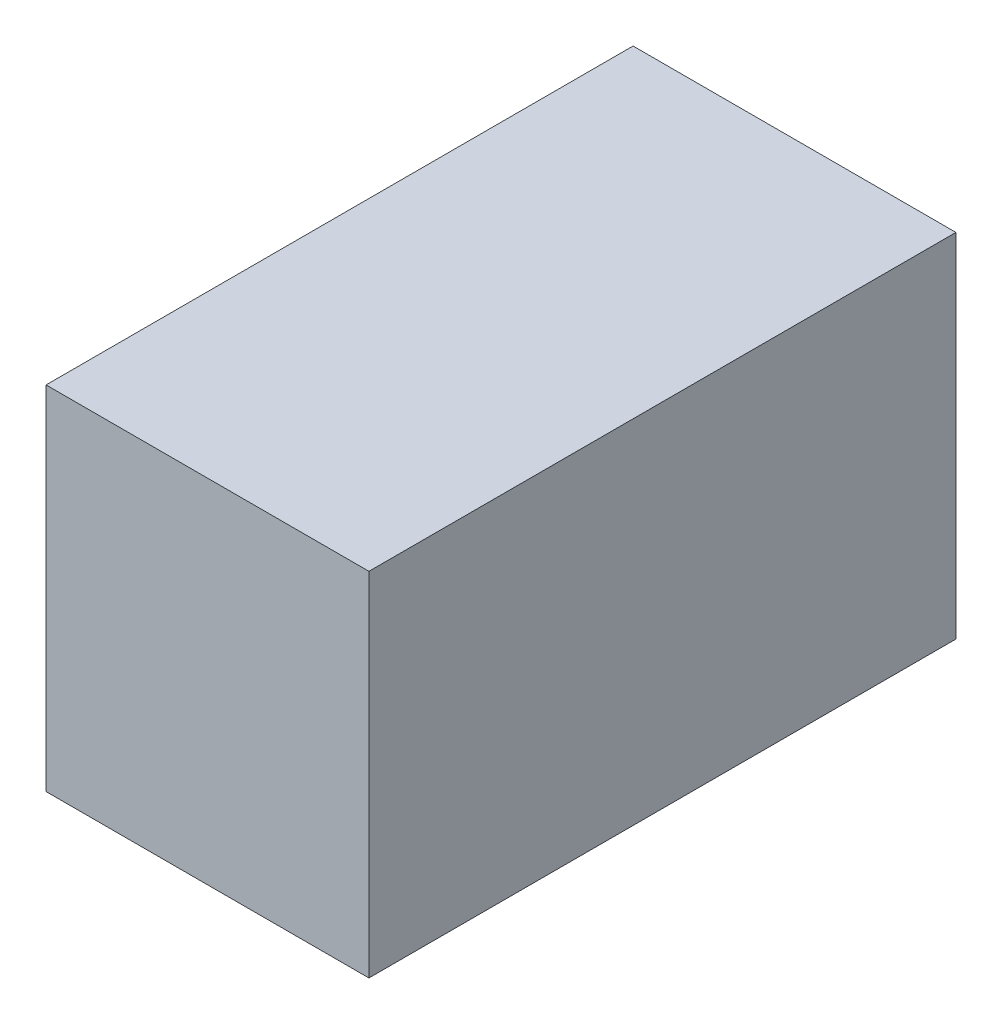
SolidWorks part; units mm, degrees
ref_plane "Front Plane" through (0, 0, 0) normal (0, 0, 1) x (1, 0, 0)
ref_plane "Top Plane" through (0, 0, 0) normal (0, 1, 0) x (1, 0, 0)
ref_plane "Right Plane" through (0, 0, 0) normal (1, 0, 0) x (0, 0, -1)
sketch "Sketch1" plane through (0, 0, 0) normal (0, 1, 0) x (1, 0, 0)
  line L1 (5.5, -10) -> (-5.5, -10)
  line L2 (5.5, -10) -> (5.5, 10)
  line L3 (5.5, 10) -> (-5.5, 10)
  line L4 (-5.5, -10) -> (-5.5, 10)
  line L5 (5.5, -10) -> (-5.5, 10) construction
  line L6 (5.5, 10) -> (-5.5, -10) construction
  point P0 (0, 0)
  dimension "D1" = 20
  dimension "D2" = 11
extrude "Boss-Extrude1" add sketch "Sketch1" along normal blind 12
